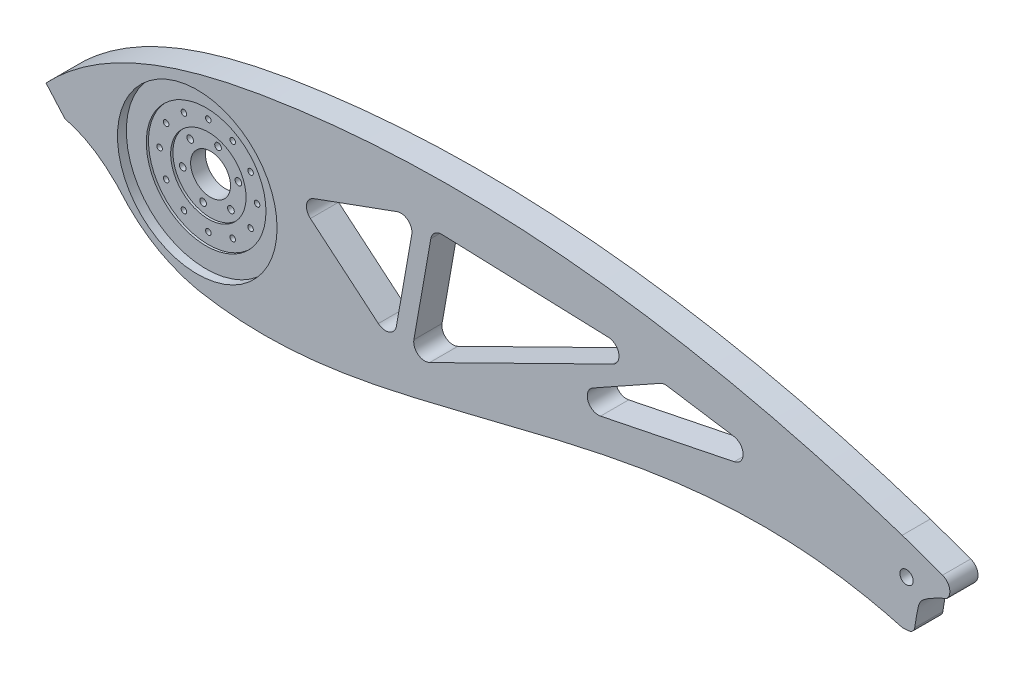
SolidWorks part; units mm, degrees
ref_plane "Front Plane" through (0, 0, 0) normal (0, 0, 1) x (1, 0, 0)
ref_plane "Top Plane" through (0, 0, 0) normal (0, 1, 0) x (1, 0, 0)
ref_plane "Right Plane" through (0, 0, 0) normal (1, 0, 0) x (0, 0, -1)
sketch "Croquis2" plane through (0, 0, 0) normal (0, 0, 1) x (1, 0, 0)
  line L3 (-68.2371, 4.5591) -> (-59.6532, -5.204)
  line L4 (318.0038, 21.0005) -> (336.1896, 14.479)
  arc A3 (338, 6.2) -> (336.1896, 14.479) centre (334.5018, 9.7725) ccw
  arc A4 (318.0038, -15.0543) -> (321.0712, -14.8533) centre (318.0038, 8.4457) ccw
  arc A5 (323.6438, -12.3415) -> (321.0712, -14.8533) centre (320.6796, -11.8789) cw
  spline S0 degree 3 poles (318.0038, 21.0005) (228.6128, 50.5792) (93.8377, 69.7133) (-40.8977, 33.4698) (-68.2371, 4.5591) knots 0 0 0 0 0.707437 1 1 1 1
  spline S2 degree 2 poles (0, -42) (-20.5144, -37.2835) (-33.9603, -21.8098) knots 0 0 0 1 1 1
  spline S3 degree 3 poles (0, -42) (34.8041, -48.5839) (140.6016, -28.663) (242.0663, 5.9793) (318.0038, -15.0543) knots 0 0 0 0 0.3223 1 1 1 1
  spline S4 degree 3 poles (338, 6.2) (337.9648, 6.1656) (334.3917, 4.9267) (325.4566, -0.139) (325.2312, -2.1702) (323.6438, -12.3415) knots 0.205944 0.205944 0.205944 0.205944 0.210384 0.5344 0.959977 0.959977 0.959977 0.959977
  spline S5 degree 3 poles (-31, -25) (-39.3963, -15.1385) (-48.3856, -7.8346) (-59.6532, -5.204) knots 0.532563 0.532563 0.532563 0.532563 1 1 1 1
  point P27 (53.7401, -43.3372)
  dimension "D1" = 5
  dimension "D2" = 3
  dimension "D3" = 13
extrude "Saliente-Extruir1" add sketch "Croquis2" along normal blind 12.7 contours S5 S2 S3 A4 A5 S4 A3 L4 S0 L3
sketch "Croquis5" plane through (0, 0, 12.7) normal (0, 0, 1) x (1, 0, 0)
  circle A0 centre (0, 0) radius 36
sketch "Croquis6" plane through (0, 0, 12.7) normal (0, 0, 1) x (1, 0, 0)
  circle A1 centre (0, 22) radius 1.25
  circle A2 centre (11, 19.0526) radius 1.25
  circle A3 centre (19.0526, 11) radius 1.25
  circle A4 centre (22, 0) radius 1.25
  circle A5 centre (19.0526, -11) radius 1.25
  circle A6 centre (11, -19.0526) radius 1.25
  circle A7 centre (0, -22) radius 1.25
  circle A8 centre (-11, -19.0526) radius 1.25
  circle A9 centre (-19.0526, -11) radius 1.25
  circle A10 centre (-22, 0) radius 1.25
  circle A11 centre (-19.0526, 11) radius 1.25
  circle A12 centre (-11, 19.0526) radius 1.25
  point P28 (0, 0)
  dimension "D1" = 12
sketch "Croquis8" plane through (0, 0, 12.7) normal (0, 0, 1) x (1, 0, 0)
  circle A0 centre (319.9513, 5.5848) radius 3
sketch "Croquis12" plane through (0, 0, 0) normal (0, 0, -1) x (-1, 0, 0)
  circle A0 centre (0, 0) radius 17
  circle A1 centre (0, 0) radius 26
sketch "Croquis13" plane through (0, 0, 0) normal (0, 0, -1) x (-1, 0, 0)
  circle A6 centre (12.557, -3.3646) radius 1.5
  circle A7 centre (3.3646, -12.557) radius 1.5
  circle A8 centre (-9.1924, -9.1924) radius 1.5
  circle A10 centre (9.1924, 9.1924) radius 1.5
  circle A11 centre (-12.557, 3.3646) radius 1.5
  circle A12 centre (-3.3646, 12.557) radius 1.5
  point P14 (0, 0)
  point P15 (0, 0)
  dimension "D1" = 6
sketch "Croquis15" plane through (0, 0, 12.7) normal (0, 0, 1) x (1, 0, 0)
  line L0 (97.7235, -12.7568) -> (105.3612, 30.5587)
  line L1 (110.4597, 34.6874) -> (185.414, 32.07)
  line L2 (89.8227, -11.4945) -> (96.7686, 27.8978)
  line L3 (90.1344, 33.4645) -> (52.5467, 19.7837)
  line L4 (51.0429, 11.255) -> (81.6847, -14.4565)
  line L5 (187.4496, 22.588) -> (104.8576, -18.1101)
  line L6 (178.4856, 8.7617) -> (208.7865, 25.7186)
  line L7 (211.9904, 26.297) -> (242.0099, 21.667)
  line L8 (242.2488, 11.8267) -> (181.9285, -0.5003)
  circle A0 centre (77, 11.075) radius 10 construction
  arc A1 (89.8227, -11.4945) -> (81.6847, -14.4565) centre (84.8986, -10.6263) cw
  arc A2 (52.5467, 19.7837) -> (51.0429, 11.255) centre (54.2568, 15.0852) ccw
  arc A3 (96.7686, 27.8978) -> (90.1344, 33.4645) centre (91.8445, 28.766) ccw
  arc A4 (97.7235, -12.7568) -> (104.8576, -18.1101) centre (102.6475, -13.625) ccw
  arc A5 (105.3612, 30.5587) -> (110.4597, 34.6874) centre (110.2852, 29.6905) cw
  arc A6 (185.414, 32.07) -> (187.4496, 22.588) centre (185.2395, 27.073) cw
  arc A7 (178.4856, 8.7617) -> (181.9285, -0.5003) centre (180.9274, 4.3985) ccw
  arc A8 (242.0099, 21.667) -> (242.2488, 11.8267) centre (241.2477, 16.7254) cw
  arc A9 (208.7865, 25.7186) -> (211.9904, 26.297) centre (211.2282, 21.3554) cw
  dimension "D1" = 5
  dimension "D2" = 5
  dimension "D3" = 5
  dimension "D4" = 3
  dimension "D5" = 8
extrude "Cortar-Extruir20" cut sketch "Croquis15" against normal blind 62
extrude "Cortar-Extruir21" cut sketch "Croquis12" against normal blind 4
extrude "Cortar-Extruir22" cut sketch "Croquis6" against normal blind 29
extrude "Cortar-Extruir23" cut sketch "Croquis13" against normal blind 29 contours A12 | A10 | A6 | A7 | A8 | A11
extrude "Cortar-Extruir27" cut sketch "Croquis8" against normal blind 64 contours A0
extrude "Cortar-Extruir28" cut sketch "Croquis5" against normal blind 4 contours A0
sketch "Croquis22" plane through (0, 0, 8.7) normal (0, 0, 1) x (1, 0, 0)
  circle A0 centre (0, 0) radius 27
extrude "Cortar-Extruir32" cut sketch "Croquis22" against normal blind 1
sketch "Croquis23" plane through (0, 0, 7.7) normal (0, 0, 1) x (1, 0, 0)
  circle A0 centre (0, 0) radius 17
extrude "Cortar-Extruir33" cut sketch "Croquis23" against normal blind 1
sketch "Croquis24" plane through (0, 0, 0) normal (0, 0, -1) x (-1, 0, 0)
  circle A0 centre (0, 0) radius 9
extrude "Cortar-Extruir34" cut sketch "Croquis24" against normal blind 67
